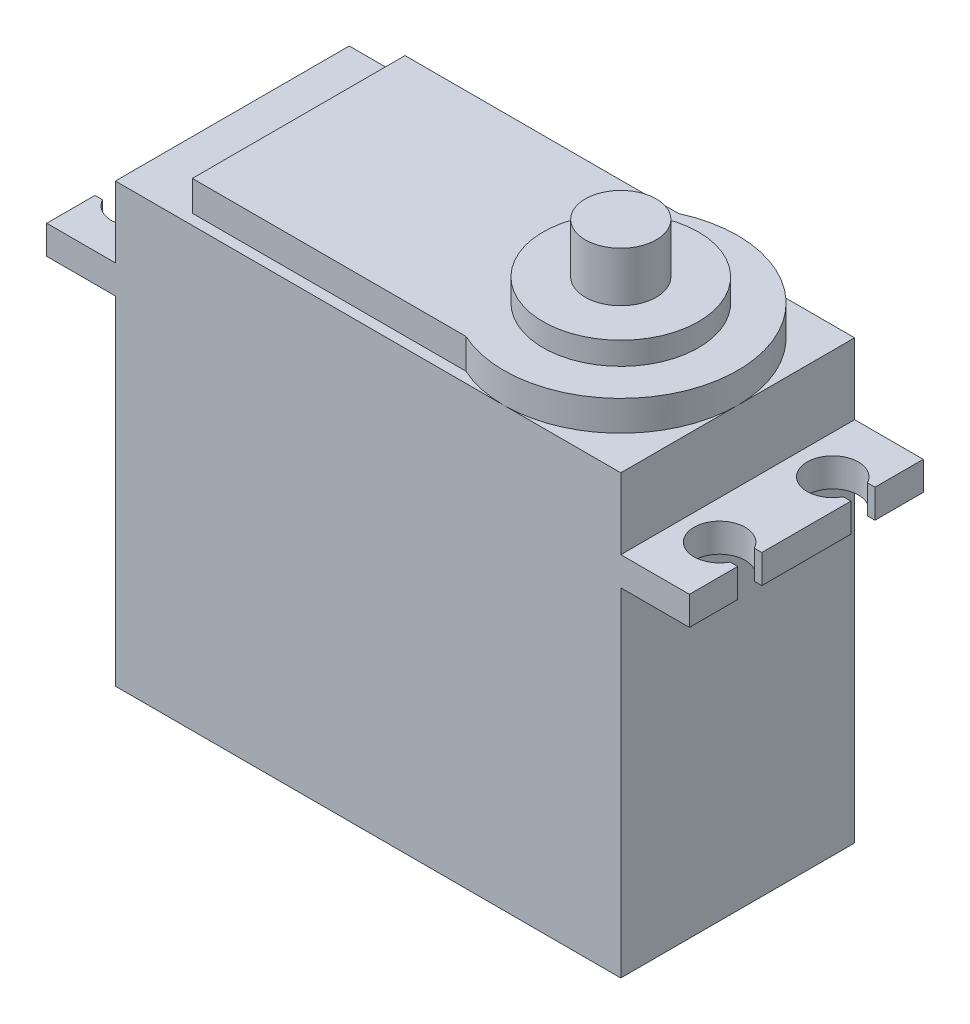
SolidWorks part; units mm, degrees
ref_plane "Front Plane" through (0, 0, 0) normal (0, 0, 1) x (1, 0, 0)
ref_plane "Top Plane" through (0, 0, 0) normal (0, 1, 0) x (1, 0, 0)
ref_plane "Right Plane" through (0, 0, 0) normal (1, 0, 0) x (0, 0, -1)
sketch "Sketch2" plane through (0, 0, 0) normal (0, 1, 0) x (1, 0, 0)
  line L0 (27.051, 0) -> (-27.051, 0) construction
  line L1 (-27.051, -9.8425) -> (27.051, -9.8425)
  line L2 (-27.051, -9.8425) -> (-27.051, -5.7785)
  line L3 (-27.051, 9.8425) -> (27.051, 9.8425)
  line L4 (27.051, -9.8425) -> (27.051, -5.7785)
  line L5 (-27.051, -9.8425) -> (27.051, 9.8425) construction
  line L6 (-27.051, 9.8425) -> (27.051, -9.8425) construction
  line L7 (26.416, -3.7465) -> (27.051, -3.7465)
  line L8 (26.416, -5.7785) -> (27.051, -5.7785)
  line L9 (26.416, 5.7785) -> (27.051, 5.7785)
  line L10 (26.416, 3.7465) -> (27.051, 3.7465)
  line L11 (27.051, -3.7465) -> (27.051, 3.7465)
  line L12 (27.051, 5.7785) -> (27.051, 9.8425)
  line L13 (0, 9.8425) -> (0, -9.8425) construction
  line L14 (-26.416, -5.7785) -> (-27.051, -5.7785)
  line L15 (-26.416, -3.7465) -> (-27.051, -3.7465)
  line L16 (-26.416, 3.7465) -> (-27.051, 3.7465)
  line L17 (-26.416, 5.7785) -> (-27.051, 5.7785)
  line L18 (-27.051, 5.7785) -> (-27.051, 9.8425)
  line L19 (-27.051, -3.7465) -> (-27.051, 3.7465)
  arc A0 (26.416, -3.7465) -> (26.416, -5.7785) centre (24.511, -4.7625) ccw
  arc A1 (26.416, 3.7465) -> (26.416, 5.7785) centre (24.511, 4.7625) cw
  arc A2 (-26.416, -3.7465) -> (-26.416, -5.7785) centre (-24.511, -4.7625) cw
  arc A3 (-26.416, 3.7465) -> (-26.416, 5.7785) centre (-24.511, 4.7625) ccw
  point P0 (0, 0)
  dimension "D3" = 4.318
  dimension "D4" = 5.08
  dimension "D5" = 2.54
  dimension "D1" = 54.102
  dimension "D2" = 19.685
  dimension "D6" = 2.032
extrude "Boss-Extrude1" add sketch "Sketch2" along normal blind 2.413
sketch "Sketch3" plane through (0, 0, 0) normal (0, 1, 0) x (1, 0, 0)
  line L0 (27.051, 9.8425) -> (-27.051, 9.8425) construction
  line L1 (21.2725, -9.8425) -> (-21.2725, -9.8425)
  line L2 (21.2725, -9.8425) -> (21.2725, 9.8425)
  line L3 (21.2725, 9.8425) -> (-21.2725, 9.8425)
  line L4 (-21.2725, -9.8425) -> (-21.2725, 9.8425)
  line L5 (21.2725, -9.8425) -> (-21.2725, 9.8425) construction
  line L6 (21.2725, 9.8425) -> (-21.2725, -9.8425) construction
  point P0 (0, 0)
  dimension "D1" = 42.545
extrude "Boss-Extrude2" add sketch "Sketch3" against normal blind 28.448 and the other way blind 8.382
sketch "Sketch4" plane through (0, 8.382, 0) normal (0, 1, 0) x (1, 0, 0)
  line L0 (21.2725, 9.8425) -> (-21.2725, 9.8425) construction
  line L2 (21.2725, -9.8425) -> (21.2725, 9.8425) construction
  line L3 (-21.2725, 9.8425) -> (-21.2725, -9.8425) construction
  line L4 (-15.6845, 8.9535) -> (7.3423, 8.9535)
  line L5 (-15.6845, 8.9535) -> (-15.6845, -8.9535)
  line L6 (-15.6845, -8.9535) -> (7.3423, -8.9535)
  arc A0 (7.3423, -8.9535) -> (7.3423, 8.9535) centre (11.43, 0) ccw
  point P6 (-15.6845, 0)
  point P14 (0, 0)
  dimension "D1" = 5.588
  dimension "D2" = 17.907
extrude "Boss-Extrude3" add sketch "Sketch4" along normal blind 2.54
sketch "Sketch5" plane through (0, 10.922, 0) normal (0, 1, 0) x (1, 0, 0)
  circle A0 centre (11.43, 0) radius 6.5405
  arc A3 (7.3423, -8.9535) -> (7.3423, 8.9535) centre (11.43, 0) ccw construction
  dimension "D1" = 13.081
extrude "Boss-Extrude4" add sketch "Sketch5" along normal blind 1.905
sketch "Sketch6" plane through (0, 12.827, 0) normal (0, 1, 0) x (1, 0, 0)
  circle A0 centre (11.43, 0) radius 2.9845
  circle A1 centre (11.43, 0) radius 6.5405 construction
  dimension "D1" = 5.969
extrude "Boss-Extrude5" add sketch "Sketch6" along normal blind 4.191
